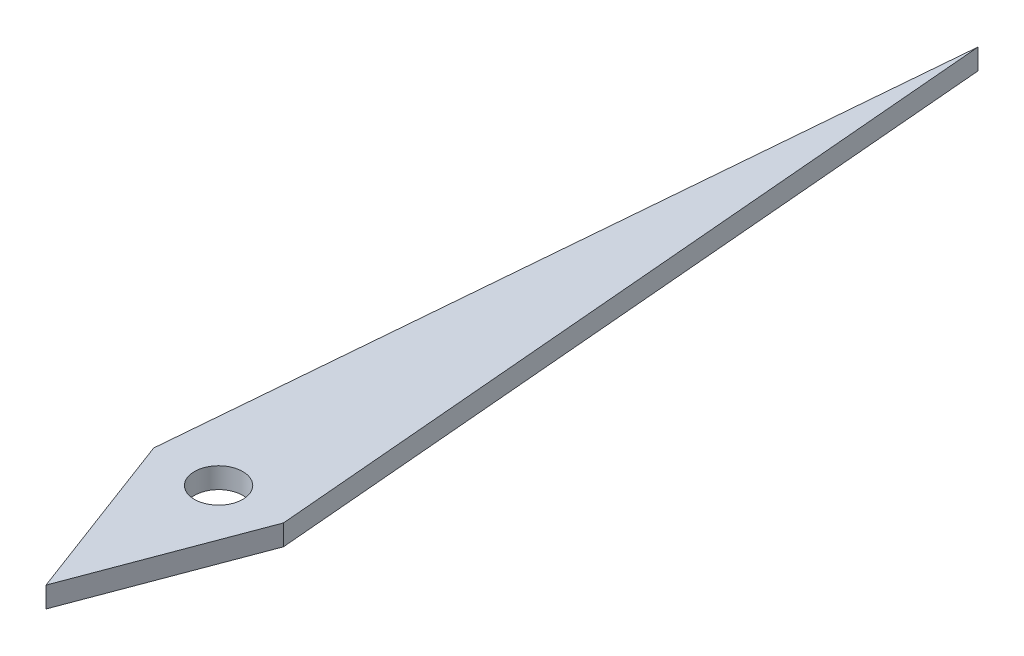
SolidWorks part; units mm, degrees
ref_plane "Front Plane" through (0, 0, 0) normal (0, 0, 1) x (1, 0, 0)
ref_plane "Top Plane" through (0, 0, 0) normal (0, 1, 0) x (1, 0, 0)
ref_plane "Right Plane" through (0, 0, 0) normal (1, 0, 0) x (0, 0, -1)
sketch "Sketch1" plane through (0, 0, 0) normal (0, 1, 0) x (1, 0, 0)
  line L4 (-0.94, 0) -> (0, 11)
  line L5 (0, 11) -> (0.94, 0)
  line L6 (0.94, 0) -> (0, -2.5)
  line L7 (0, -2.5) -> (-0.94, 0)
extrude "Boss-Extrude1" add sketch "Sketch1" along normal blind 0.3
sketch "Sketch2" plane through (0, 0.3, 0) normal (0, 1, 0) x (1, 0, 0)
  circle A0 centre (0, 0) radius 0.35
extrude "Cut-Extrude1" cut sketch "Sketch2" against normal blind 0.3
